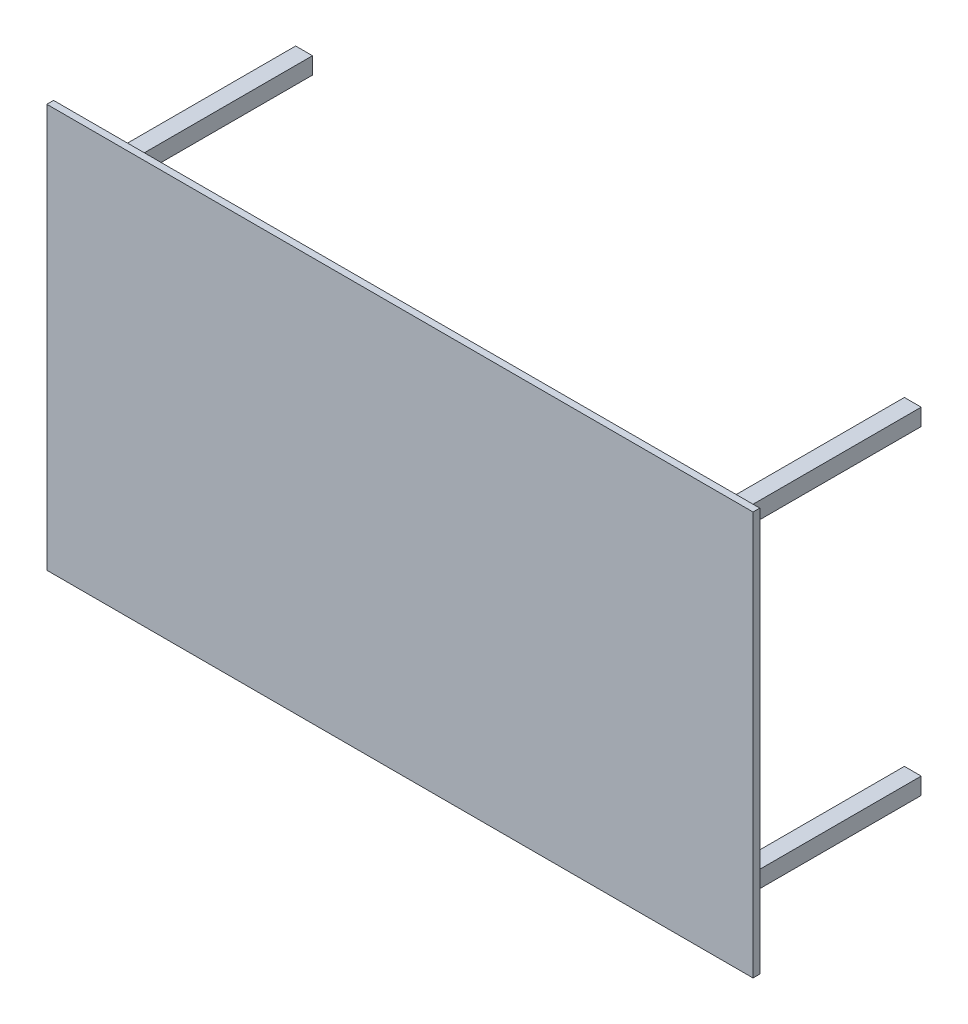
SolidWorks part; units mm, degrees
material "Pinho"
ref_plane "Plano frontal" through (0, 0, 0) normal (0, 0, 1) x (1, 0, 0)
ref_plane "Plano superior" through (0, 0, 0) normal (0, 1, 0) x (1, 0, 0)
ref_plane "Plano direito" through (0, 0, 0) normal (1, 0, 0) x (0, 0, -1)
sketch "Esboço1" plane through (0, 0, 0) normal (0, 0, 1) x (1, 0, 0)
  line L1 (-1050, 600) -> (1050, 600)
  line L2 (-1050, 600) -> (-1050, -600)
  line L3 (-1050, -600) -> (1050, -600)
  line L4 (1050, 600) -> (1050, -600)
  line L5 (-1050, 600) -> (1050, -600) construction
  line L6 (-1050, -600) -> (1050, 600) construction
  point P0 (0, 0)
  dimension "D1" = 2100
  dimension "D2" = 1200
extrude "Ressalto-extrusão1" add sketch "Esboço1" along normal blind 20
sketch "Esboço2" plane through (0, 0, 0) normal (0, 0, -1) x (-1, 0, 0)
  line L0 (0, 600) -> (0, -600) construction
  line L1 (-930, 500) -> (-880, 500)
  line L2 (-930, 500) -> (-930, 450)
  line L3 (-930, 450) -> (-880, 450)
  line L4 (-880, 500) -> (-880, 450)
  line L5 (-930, 500) -> (-880, 450) construction
  line L6 (-930, 450) -> (-880, 500) construction
  line L7 (-1050, -600) -> (-1050, 600) construction
  line L8 (930, -500) -> (880, -450) construction
  line L9 (930, -450) -> (880, -500) construction
  line L10 (880, -450) -> (880, -500)
  line L11 (930, -500) -> (880, -500)
  line L12 (930, -450) -> (930, -500)
  line L13 (-930, -450) -> (-880, -450)
  line L14 (-930, -450) -> (-930, -500)
  line L15 (-930, -500) -> (-880, -500)
  line L16 (-880, -450) -> (-880, -500)
  line L17 (-930, -450) -> (-880, -500) construction
  line L18 (-930, -500) -> (-880, -450) construction
  line L19 (930, -450) -> (880, -450)
  line L20 (930, 450) -> (880, 500) construction
  line L21 (930, 500) -> (880, 450) construction
  line L22 (880, 500) -> (880, 450)
  line L23 (930, 450) -> (880, 450)
  line L24 (930, 500) -> (930, 450)
  line L25 (-1050, 600) -> (1050, 600) construction
  line L26 (1050, -600) -> (-1050, -600) construction
  line L27 (930, 500) -> (880, 500)
  point P0 (-905, 475)
  point P10 (-905, -475)
  point P16 (905, -475)
  point P27 (905, 475)
  dimension "D1" = 50
  dimension "D2" = 50
  dimension "D3" = 100
  dimension "D4" = 170
  dimension "D5" = 50
  dimension "D6" = 50
  dimension "D7" = 170
  dimension "D8" = 100
extrude "Ressalto-extrusão2" add sketch "Esboço2" along normal blind 600
